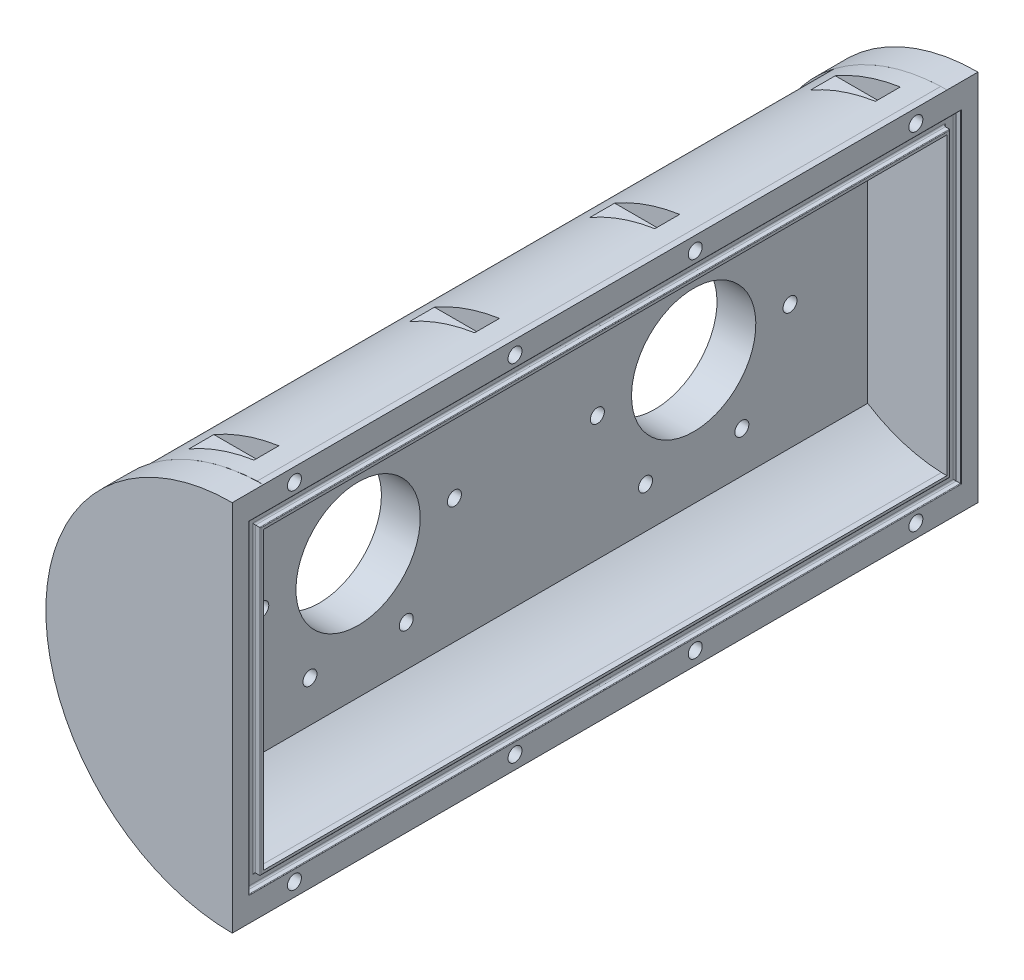
SolidWorks part; units mm, degrees
ref_plane "Front Plane" through (0, 0, 0) normal (0, 0, 1) x (1, 0, 0)
ref_plane "Top Plane" through (0, 0, 0) normal (0, 1, 0) x (1, 0, 0)
ref_plane "Right Plane" through (0, 0, 0) normal (1, 0, 0) x (0, 0, -1)
sketch "Sketch1" plane through (0, 0, 0) normal (0, 0, 1) x (1, 0, 0)
  line L0 (-170.391, 0) -> (173.2308, 0) construction
  line L14 (0, 0) -> (0, -44.1468) construction
  line L15 (0, 60) -> (-2, 60)
  line L16 (-60, -212.0739) -> (-60, 258.0529) construction
  line L17 (-38, 77.5263) -> (-38, -50.705) construction
  line L18 (-38, 44.0002) -> (-38, -44.0002)
  line L22 (0, -60) -> (-2, -60)
  line L23 (0, 47.5) -> (-1.7688, 47.5)
  line L24 (-25.5, 40.0763) -> (-25.5, -40.0763)
  line L25 (0, -47.5) -> (-1.7688, -47.5)
  line L26 (0, 47.5) -> (0, 60)
  line L28 (0, -47.5) -> (0, -60)
  arc A17 (0, 60) -> (0, -60) centre (0, 0) ccw construction
  arc A18 (-2, 60) -> (-36.0005, 47.9998) centre (0.103, -0.1258) ccw
  arc A19 (-38, 44.0002) -> (-36.0005, 47.9998) centre (-33, 44.0002) cw
  arc A20 (-2, -60) -> (-36.0005, -47.9998) centre (0.103, 0.1258) cw
  arc A21 (-38, -44.0002) -> (-36.0005, -47.9998) centre (-33, -44.0002) ccw
  arc A22 (-1.7688, 47.5) -> (-25.5, 40.0763) centre (0.103, -0.1258) ccw
  arc A23 (-25.5, 40.0763) -> (-25.5, 40.0763) centre (-25.5, 40.0763) cw
  arc A24 (-25.5, -40.0763) -> (-25.5, -40.0763) centre (-25.5, -40.0763) ccw
  arc A25 (-1.7688, -47.5) -> (-25.5, -40.0763) centre (0.103, 0.1258) cw
  point P23 (-38, 0)
  dimension "D1" = 2
  dimension "D2" = 60
  dimension "D5" = 5
  dimension "D6" = 44.0002
  dimension "D7" = 12.5
  dimension "D3" = 60
  dimension "D4" = 22
extrude "Boss-Extrude1" add sketch "Sketch1" against normal blind 110
sketch "Sketch7" plane through (0, 0, 0) normal (0, 0, 1) x (1, 0, 0)
  line L0 (0, 102.7731) -> (0, -125.6424) construction
  line L1 (130.9597, 0) -> (-140.6919, 0) construction
  line L5 (0, 60) -> (0, -60)
  arc A4 (0, 60) -> (0, -60) centre (0, 0) ccw
  point P7 (-60, 0)
  dimension "D1" = 60
extrude "Boss-Extrude3" add sketch "Sketch7" along normal blind 10 from offset 120 offset against normal yes
sketch "Sketch11" plane through (0, 0, 0) normal (-1, 0, 0) x (0, 0, -1)
  line L0 (110, -991.2181) -> (110, 49008.7819) construction
  line L2 (0, -995.6825) -> (0, 49004.3175) construction
  line L4 (110, -60) -> (0, -60) construction
  line L5 (-59.4019, 0) -> (154.8587, 0) construction
  line L7 (25, 60) -> (25, 52)
  line L9 (33, 52) -> (25, 52)
  line L34 (104, -60) -> (96, -60)
  line L35 (104, -60) -> (104, -52)
  line L36 (104, -52) -> (96, -52)
  line L37 (96, -60) -> (96, -52)
  line L38 (33, -60) -> (25, -60)
  line L39 (33, -60) -> (33, -52)
  line L40 (33, -52) -> (25, -52)
  line L41 (25, -60) -> (25, -52)
  line L49 (33, 60) -> (33, 52)
  line L50 (33, 60) -> (25, 60)
  line L51 (96, 60) -> (96, 52)
  line L52 (104, 52) -> (96, 52)
  line L53 (104, 60) -> (104, 52)
  line L54 (104, 60) -> (96, 60)
  dimension "D5" = 8
  dimension "D6" = 25
  dimension "D1" = 6
  dimension "D2" = 8
  dimension "D3" = 8
  dimension "D4" = 8
  dimension "D7" = 63
extrude "Cut-Extrude1" cut sketch "Sketch11" against normal blind 51 from offset 60
hole_wizard "M4 Clearance Hole5" positions "Sketch28" profile "Sketch27" hole size "M4" standard "ANSI Metric" end condition up to next
sketch "Sketch28" plane through (-9, 0, 0) normal (-1, 0, 0) x (0, 0, 1)
  line L0 (-104, 52) -> (-25, 52) construction
  line L2 (-104, -52) -> (-25, -52) construction
  line L4 (-100, 59.3441) -> (-100, 52) construction
  line L5 (-104, 59.3441) -> (-96, 59.3441) construction
  line L6 (-104, -59.3441) -> (-96, -59.3441) construction
  line L8 (-29, -59.3441) -> (-29, -52) construction
  line L9 (-33, -59.3441) -> (-25, -59.3441) construction
  line L10 (-33, 59.3441) -> (-25, 59.3441) construction
  line L12 (-29, 52) -> (-29, 59.3441) construction
  line L13 (-100, -52) -> (-100, -59.3441) construction
  point P0 (-100, 55.6721)
  point P2 (-29, 55.6721)
  point P4 (-100, -55.6721)
  point P6 (-29, -55.6721)
sketch "Sketch27" plane through (-9, 55.6721, -100) normal (0, 1, 0) x (0, 0, 1)
  line L0 (0, 0) -> (0, 9)
  line L1 (0, 9) -> (2.25, 9)
  line L2 (2.25, 9) -> (2.25, 0.025)
  line L3 (2.25, 0.025) -> (2.275, 0)
  line L5 (2.275, 0) -> (0, 0)
  line L6 (-2.25, 0.025) -> (-2.275, 0) construction
  line L11 (0, -6.35) -> (0, 107.95) construction
  dimension "Thru Hole Dia." = 4.5
  dimension "Thru Hole Depth" = 9
  dimension "Near C'Sink Dia." = 4.55
  dimension "Near C'Sink Angle" = 90
sketch "Sketch14" plane through (0, 0, 0) normal (1, 0, 0) x (0, 0, -1)
  line L4 (-1000, 0) -> (49000, 0) construction
  circle A0 centre (54, 0) radius 20
  dimension "D1" = 54
  dimension "D2" = 40
extrude "Cut-Extrude2" cut sketch "Sketch14" against normal blind 48 from offset 20 offset against normal yes
sketch "Sketch32" plane through (0, 0, 0) normal (1, 0, 0) x (0, 0, -1)
  line L0 (110, -47.5) -> (0, -47.5) construction
  line L1 (110, -40.0763) -> (110, -47.5) construction
  line L2 (110, -47.5) -> (110, 47.5) construction
  line L3 (110, 47.5) -> (110, 40.0763) construction
  line L4 (110, 47.5) -> (0, 47.5) construction
  line L5 (110, -47.5) -> (0, -47.5)
  line L6 (110, -40.0763) -> (110, -47.5)
  line L7 (110, -47.5) -> (110, 47.5)
  line L8 (110, 47.5) -> (110, 40.0763)
  line L9 (110, 47.5) -> (0, 47.5)
  line L10 (110, 48.5) -> (0, 48.5)
  line L11 (110, 48.5) -> (111, 48.5)
  line L12 (111, 48.5) -> (111, -48.5)
  line L13 (111, -48.5) -> (0, -48.5)
  line L14 (0, -47.5) -> (0, -60) construction
  line L15 (114.5, -52) -> (0, -52)
  line L16 (114.5, 52) -> (114.5, -52)
  line L17 (110, 52) -> (114.5, 52)
  line L18 (110, 52) -> (0, 52)
  line L19 (0, 52) -> (0, 48.5)
  line L20 (0, -52) -> (0, -48.5)
  dimension "D2" = 1
  dimension "D3" = 1
  dimension "D4" = 3.5
  dimension "D1" = 1
extrude "Cut-Extrude4" cut sketch "Sketch32" against normal blind 2 and the other way through all contours L18 L19 L10 L11 L12 L13 L20 L15 L16 L17
ref_plane "Mid dome" through (0, 0, -54) normal (0, 0, 1) x (1, 0, 0)
sketch "Sketch33" plane through (0, 0, -54) normal (0, 0, 1) x (1, 0, 0)
  line L0 (11.8446, 0) -> (-82.0476, 0) construction
  line L1 (-38, 44.0002) -> (-38, -44.0002) construction
  line L2 (-38, -21) -> (-33, -21)
  line L3 (-38, -21) -> (-38, -27)
  line L4 (-38, -27) -> (-33, -27)
  line L5 (-33, -21) -> (-33, -27)
  dimension "D1" = 5
  dimension "D2" = 6
  dimension "D3" = 21
revolve "Cut-Revolve1" cut sketch "Sketch33" angle 360 about L0
hole_wizard "M4 Clearance Hole3" positions "Sketch25" profile "Sketch26" hole size "M4" standard "ANSI Metric" end condition through all
sketch "Sketch25" plane through (-38, 0, 0) normal (-1, 0, 0) x (0, 0, 1)
  line L0 (-27, 0) -> (-81, 0) construction
  line L1 (-38, 0) -> (-38, 42.8885) construction
  circle A2 centre (-54, 0) radius 27 construction
  circle A3 centre (-54, 0) radius 27 construction
  point P66 (-85, 0)
  dimension "D1" = 4
  dimension "D2" = 85
sketch "Sketch26" plane through (-38, 0, -85) normal (0, 1, 0) x (0, 0, 1)
  line L0 (0, 0) -> (0, 38)
  line L1 (0, 38) -> (2.25, 38)
  line L2 (2.25, 38) -> (2.25, 0.025)
  line L3 (2.25, 0.025) -> (2.275, 0)
  line L5 (2.275, 0) -> (0, 0)
  line L6 (-2.25, 0.025) -> (-2.275, 0) construction
  line L11 (0, -6.35) -> (0, 107.95) construction
  dimension "Thru Hole Dia." = 4.5
  dimension "Thru Hole Depth" = 38
  dimension "Near C'Sink Dia." = 4.55
  dimension "Near C'Sink Angle" = 90
pattern_circular "CirPattern7" count 6 over 360 about axis through (0, 0, -54) along (1, 0, 0) of "M4 Clearance Hole3"
fillet "Fillet1" radius 0.5 6 edges at (-2, -52, -57.25) (-2, 0, -114.5) (-2, 52, -57.25) (-2, 48.5, -55.5) (-2, 0, -111) (-2, -48.5, -55.5)
fillet "Fillet2" radius 0.2 8 edges at (0, -52, -57.25) (0, -48.5, -55.5) (0, 0, -111) (0, 0, -114.5) (0, 48.5, -55.5) (0, 52, -57.25) (-33, 21, -54) (-33, 27, -54)
sketch "Sketch36" plane through (-38, 0, 0) normal (-1, 0, 0) x (0, 0, 1)
  line L0 (-20.725, 0) -> (-87.275, 0) construction
  line L1 (-20.725, 0) -> (-25.275, 0) construction
  line L2 (-120, 12.0412) -> (-110, 12.0412) construction
  line L3 (-120, 60) -> (-120, -60) construction
  line L4 (-110, 44.0002) -> (-110, -44.0002) construction
  line L6 (-82.75, 0) -> (-81, 0) construction
  line L7 (-87.275, 0) -> (-82.75, 0) construction
  circle A0 centre (-23, 0) radius 2.275 construction
  circle A5 centre (-85, 0) radius 2.25 construction
  circle A6 centre (-54, 0) radius 27 construction
  circle A7 centre (-85, 0) radius 2.275 construction
  point P2 (-23, 0)
  point P18 (-54, 0)
mirror "Mirror_mid" about plane through (0, 0, 0) normal (0, 0, 1) of "Boss-Extrude1", "Boss-Extrude3", "Cut-Extrude1", "M4 Clearance Hole5", "Cut-Extrude2", "Cut-Extrude4", "Cut-Revolve1", "M4 Clearance Hole3", "CirPattern7", "Fillet1", "Fillet2"
